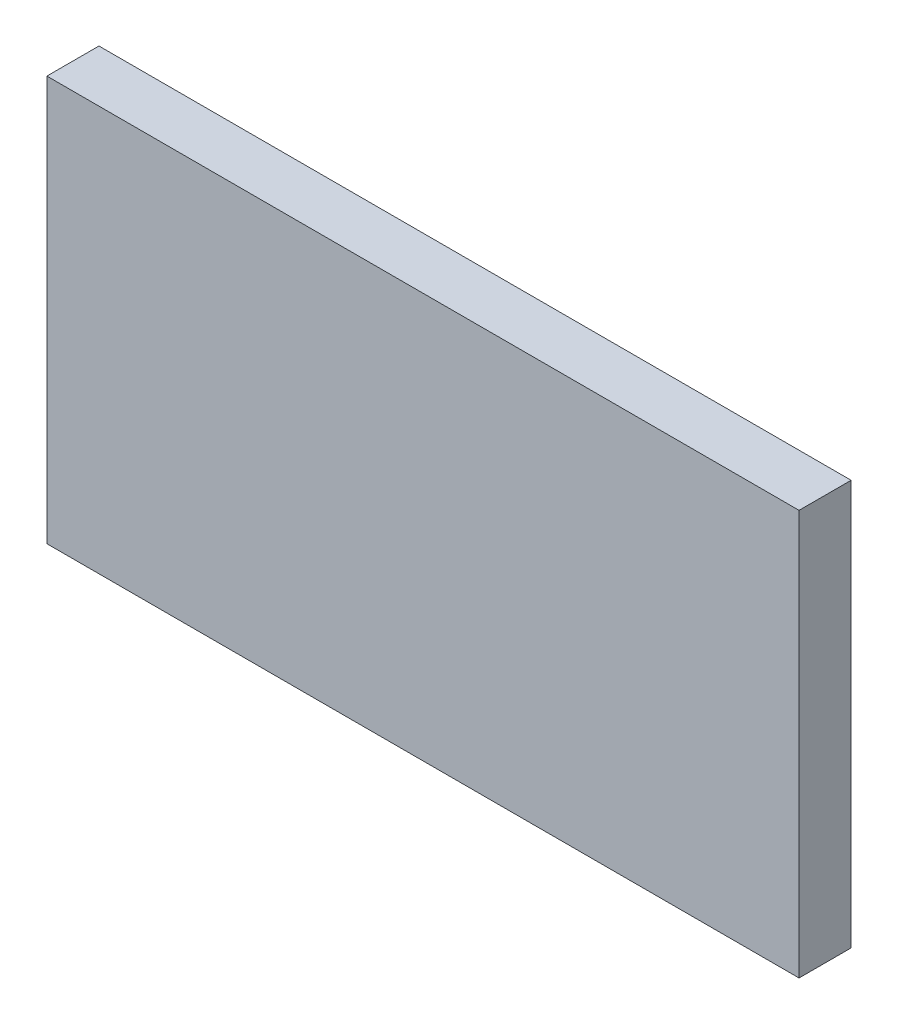
SolidWorks part; units mm, degrees
material "ABS"
ref_plane "Front Plane" through (0, 0, 0) normal (0, 0, 1) x (1, 0, 0)
ref_plane "Top Plane" through (0, 0, 0) normal (0, 1, 0) x (1, 0, 0)
ref_plane "Right Plane" through (0, 0, 0) normal (1, 0, 0) x (0, 0, -1)
sketch "Sketch1" plane through (0, 0, 0) normal (0, 0, 1) x (1, 0, 0)
  line L1 (-79.3474, 71.8714) -> (50.6526, 71.8714)
  line L2 (-79.3474, 71.8714) -> (-79.3474, 1.8714)
  line L3 (-79.3474, 1.8714) -> (50.6526, 1.8714)
  line L4 (50.6526, 71.8714) -> (50.6526, 1.8714)
  dimension "D1" = 130
  dimension "D2" = 70
extrude "Boss-Extrude1" add sketch "Sketch1" along normal blind 9
